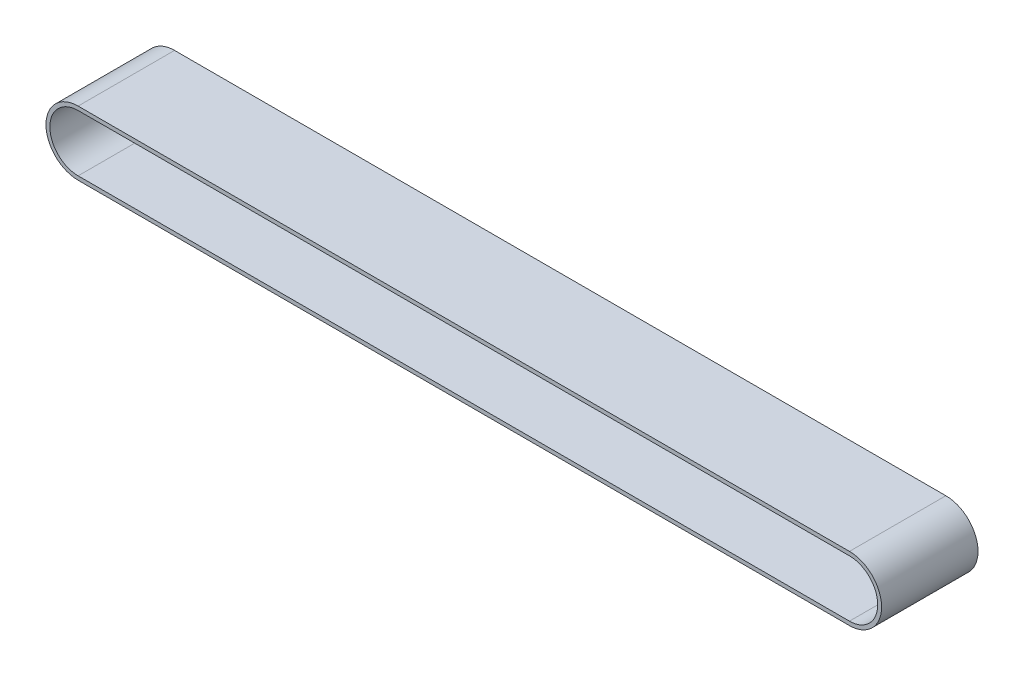
SolidWorks part; units mm, degrees
material "PVC皮带"
ref_plane "Front Plane" through (0, 0, 0) normal (0, 0, 1) x (1, 0, 0)
ref_plane "Top Plane" through (0, 0, 0) normal (0, 1, 0) x (1, 0, 0)
ref_plane "Right Plane" through (0, 0, 0) normal (1, 0, 0) x (0, 0, -1)
sketch "Sketch1" plane through (0, 0, 0) normal (0, 0, 1) x (1, 0, 0)
  line L0 (0, 0) -> (1200, 0) construction
  line L1 (0, 50) -> (1200, 50)
  line L2 (0, -50) -> (1200, -50)
  line L3 (0, 0) -> (149.2779, 0)
  line L4 (0, 44) -> (1200, 44)
  line L5 (0, -44) -> (1200, -44)
  arc A0 (0, 50) -> (0, -50) centre (0, 0) ccw
  arc A1 (1200, -50) -> (1200, 50) centre (1200, 0) ccw
  arc A2 (1200, -44) -> (1200, 44) centre (1200, 0) ccw
  arc A3 (0, 44) -> (0, -44) centre (0, 0) ccw
  point P3 (600, 0)
  dimension "D2" = 50
  dimension "D1" = 0
  dimension "D3" = 1200
  dimension "D4" = 6
extrude "Boss-Extrude1" add sketch "Sketch1" along normal mid plane 150 contours L2 A1 L1 A0 A3 L4 A2 L5
